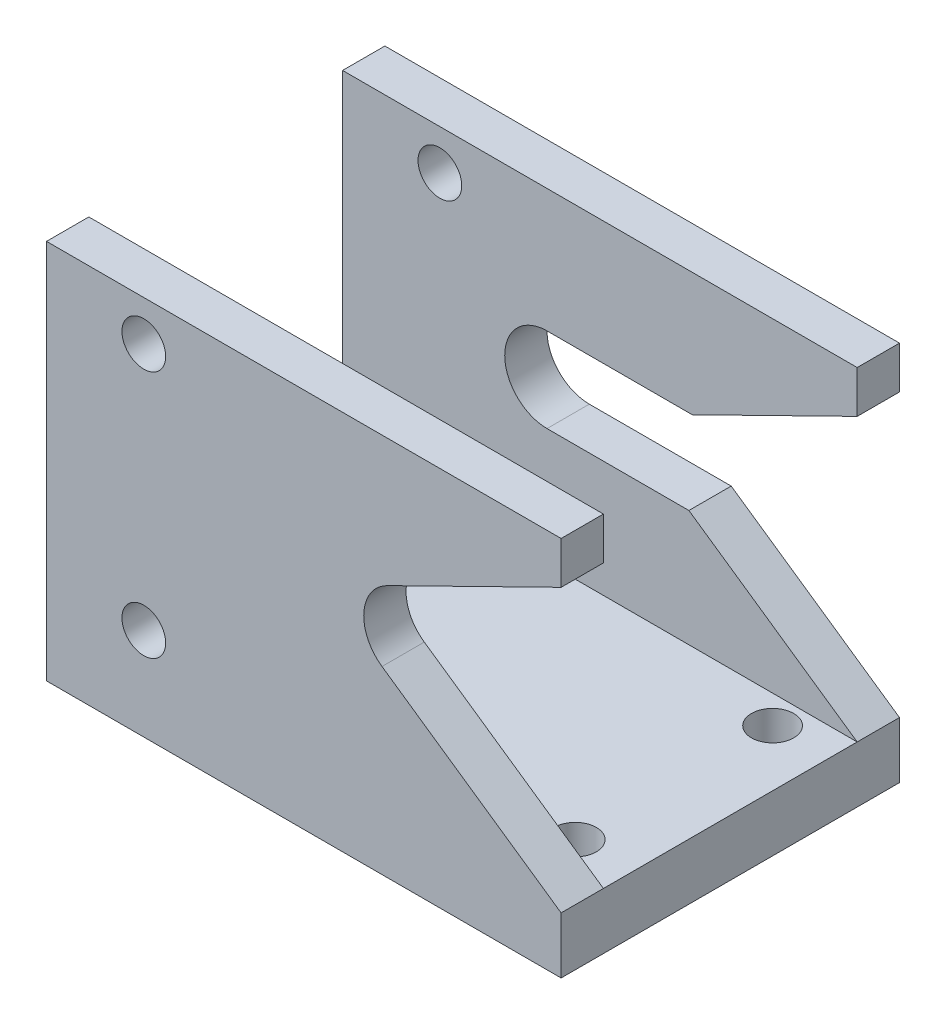
SolidWorks part; units mm, degrees
ref_plane "Front Plane" through (0, 0, 0) normal (0, 0, 1) x (1, 0, 0)
ref_plane "Top Plane" through (0, 0, 0) normal (0, 1, 0) x (1, 0, 0)
ref_plane "Right Plane" through (0, 0, 0) normal (1, 0, 0) x (0, 0, -1)
sketch "Sketch1" plane through (0, 0, 0) normal (0, 1, 0) x (1, 0, 0)
  line L1 (0, 0) -> (36.5, 0)
  line L2 (0, 0) -> (0, 24)
  line L3 (0, 24) -> (36.5, 24)
  line L4 (36.5, 0) -> (36.5, 24)
  dimension "D1" = 36.5
  dimension "D2" = 24
extrude "Boss-Extrude1" add sketch "Sketch1" along normal blind 4
sketch "Sketch2" plane through (0, 4, 0) normal (0, 1, 0) x (1, 0, 0)
  line L0 (0, 24) -> (0, 0) construction
  line L1 (0, 3) -> (36.5, 3)
  line L2 (0, 3) -> (0, 0)
  line L3 (0, 0) -> (36.5, 0)
  line L4 (36.5, 3) -> (36.5, 0)
  line L5 (36.5, 0) -> (36.5, 24) construction
  line L6 (36.5, 21) -> (0, 21)
  line L7 (36.5, 21) -> (36.5, 24)
  line L8 (36.5, 24) -> (0, 24)
  line L9 (0, 21) -> (0, 24)
  dimension "D1" = 3
  dimension "D2" = 3
extrude "Boss-Extrude2" add sketch "Sketch2" along normal blind 23
sketch "Sketch3" plane through (0, 0, 0) normal (0, 0, 1) x (1, 0, 0)
  line L0 (36.5, 27) -> (36.5, 0) construction
  line L1 (36.5, 27) -> (36.5, 0)
  line L2 (23.7942, 12.7821) -> (36.5, 4)
  line L3 (0, 0) -> (36.5, 0) construction
  line L4 (36.5, 23.9972) -> (24.1771, 17.9426)
  circle A0 centre (25.5, 15.25) radius 3
  circle A1 centre (6.9, 6.55) radius 1.55
  circle A2 centre (6.9, 24.15) radius 1.55
  dimension "D1" = 6
  dimension "D2" = 11
  dimension "D3" = 15.25
  dimension "D4" = 4
  dimension "D7" = 3.1
  dimension "D8" = 6.55
  dimension "D9" = 17.6
  dimension "D10" = 29.6
  dimension "D11" = 29.6
  dimension "D12" = 3.1
  dimension "D5" = 15.4455
  dimension "D6" = 13.73
extrude "Cut-Extrude2" cut sketch "Sketch3" against normal through all contours A0 | A0 L2 L1 L4 | A2 | A1
sketch "Sketch6" plane through (0, 4, 0) normal (0, 1, 0) x (1, 0, 0)
  line L0 (18.25, 24) -> (18.25, 0) construction
  line L1 (36.5, 24) -> (0, 24) construction
  line L2 (0, 0) -> (36.5, 0) construction
  line L3 (0, 12) -> (36.5, 12) construction
  line L4 (0, 21) -> (0, 3) construction
  line L5 (36.5, 3) -> (36.5, 21) construction
  circle A0 centre (4, 19) radius 1.5
  circle A1 centre (32.5, 19) radius 1.5
  circle A2 centre (32.5, 5) radius 1.5
  circle A3 centre (4, 5) radius 1.5
  dimension "D1" = 3
  dimension "D2" = 4
  dimension "D3" = 5
extrude "Cut-Extrude4" cut sketch "Sketch6" against normal through all
sketch "Sketch8" plane through (0, 0, -24) normal (0, 0, -1) x (-1, 0, 0)
  line L0 (-36.5, 27) -> (-36.5, 23.9972) construction
  line L2 (-36.5, 0) -> (0, 0) construction
  line L3 (-14.5, 18.25) -> (-24.8028, 18.25)
  line L4 (-36.5, 23.9972) -> (-24.1771, 17.9426) construction
  line L5 (-14.5, 12.25) -> (-24.5641, 12.25)
  line L6 (-23.7942, 12.7821) -> (-36.5, 4) construction
  circle A0 centre (-14.5, 15.25) radius 3
  line M4 (-36.5, 23.9972) -> (-24.1771, 17.9426)
  arc M5 (-24.1771, 17.9426) -> (-23.7942, 12.7821) centre (-25.5, 15.25) cw
  line M6 (-23.7942, 12.7821) -> (-36.5, 4)
  line M8 (-36.5, 0) -> (0, 0)
  dimension "D1" = 6
  dimension "D2" = 22
  dimension "D3" = 15.25
extrude "Cut-Extrude5" cut sketch "Sketch8" against normal up to next contours A0 L3 L5 M4 M5 M6 | A0 M8
